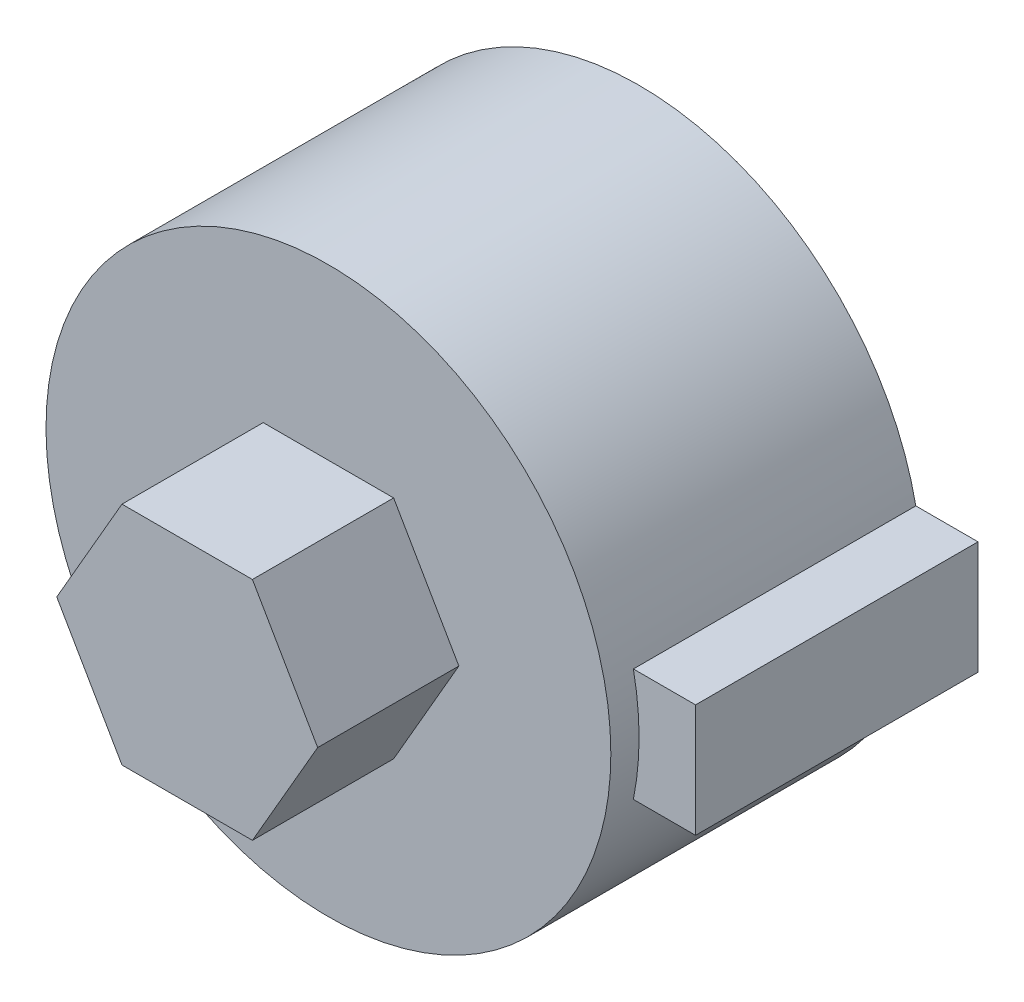
SolidWorks part; units mm, degrees
ref_plane "前视基准面" through (0, 0, 0) normal (0, 0, 1) x (1, 0, 0)
ref_plane "上视基准面" through (0, 0, 0) normal (0, 1, 0) x (1, 0, 0)
ref_plane "右视基准面" through (0, 0, 0) normal (1, 0, 0) x (0, 0, -1)
sketch "Sketch1" plane through (0, 0, 0) normal (0, 0, 1) x (1, 0, 0)
  line L0 (0, 0) -> (31.1678, 0) construction
  line L1 (12, 2) -> (12, -2)
  line L2 (12, 2) -> (9.798, 2)
  line L3 (12, -2) -> (9.798, -2)
  arc A0 (9.798, 2) -> (9.798, -2) centre (0, 0) ccw
  circle A1 centre (0, 0) radius 5
  dimension "D1" = 4
  dimension "D3" = 12
  dimension "D4" = 20
  dimension "D5" = 10
  dimension "D2" = 2
extrude "Boss-Extrude1" add sketch "Sketch1" along normal blind 10
sketch "Sketch2" plane through (0, 0, 10) normal (0, 0, 1) x (1, 0, 0)
  circle A0 centre (0, 0) radius 10
extrude "Boss-Extrude2" add sketch "Sketch2" along normal blind 1
sketch "Sketch3" plane through (0, 0, 11) normal (0, 0, 1) x (1, 0, 0)
  line L7 (4.6188, 0) -> (2.3094, 4)
  line L8 (2.3094, 4) -> (-2.3094, 4)
  line L9 (-2.3094, 4) -> (-4.6188, 0)
  line L10 (-4.6188, 0) -> (-2.3094, -4)
  line L11 (-2.3094, -4) -> (2.3094, -4)
  line L12 (2.3094, -4) -> (4.6188, 0)
  circle A0 centre (0, 0) radius 4 construction
extrude "Boss-Extrude3" add sketch "Sketch3" along normal blind 5
